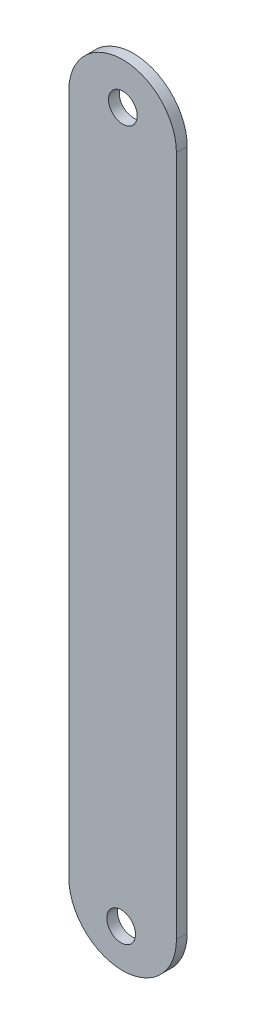
SolidWorks part; units mm, degrees
ref_plane "Front Plane" through (0, 0, 0) normal (0, 0, 1) x (1, 0, 0)
ref_plane "Top Plane" through (0, 0, 0) normal (0, 1, 0) x (1, 0, 0)
ref_plane "Right Plane" through (0, 0, 0) normal (1, 0, 0) x (0, 0, -1)
sketch "Sketch1" plane through (0, 0, 0) normal (0, 0, 1) x (1, 0, 0)
  line L0 (-18.7315, 57.2093) -> (-18.7315, -37.7907)
  line L1 (-3.7315, 57.2093) -> (-3.7315, -37.7907)
  arc A0 (-18.7315, 57.2093) -> (-3.7315, 57.2093) centre (-11.2315, 57.2093) cw
  arc A1 (-18.7315, -37.7907) -> (-3.7315, -37.7907) centre (-11.2315, -37.7907) ccw
  dimension "D1" = 15
  dimension "D2" = 95
extrude "Boss-Extrude1" add sketch "Sketch1" along normal blind 1.5
sketch "Sketch2" plane through (0, 0, 1.5) normal (0, 0, 1) x (1, 0, 0)
  circle A0 centre (-11.2029, 58.911) radius 2
  circle A1 centre (-11.4404, -40.0294) radius 2
  dimension "D1" = 4
  dimension "D2" = 4
extrude "Cut-Extrude2" cut sketch "Sketch2" against normal blind 1.5
